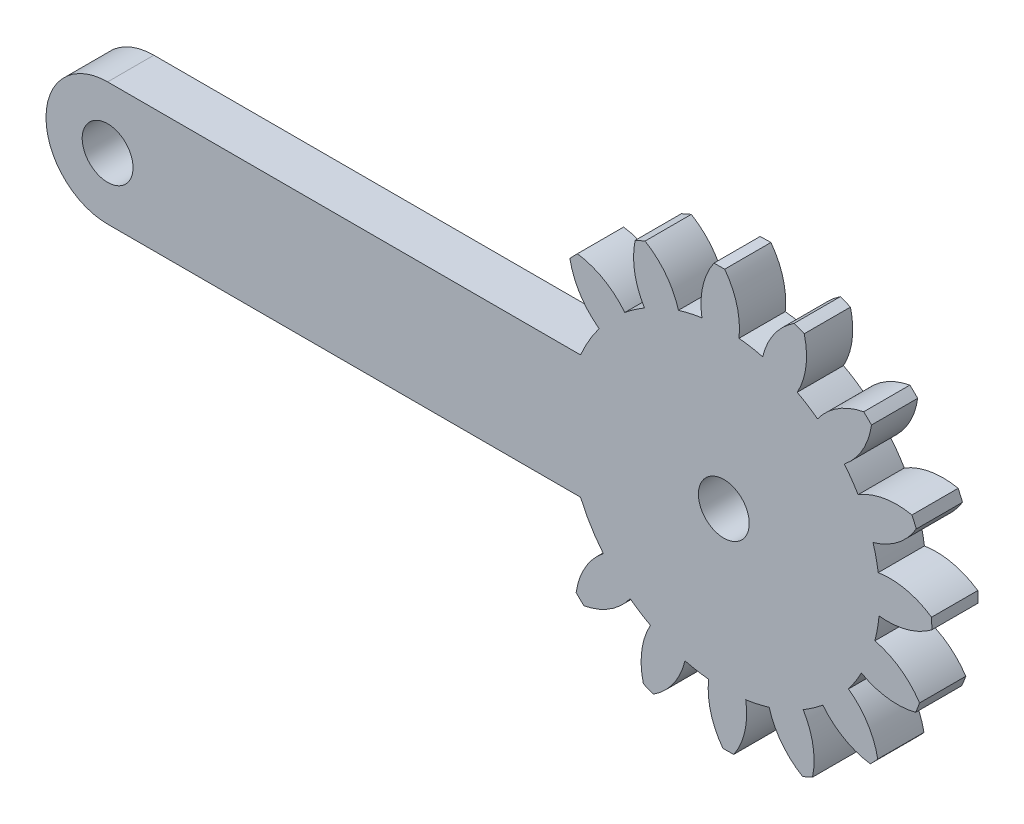
SolidWorks part; units mm, degrees
ref_plane "Front Plane" through (0, 0, 0) normal (0, 0, 1) x (1, 0, 0)
ref_plane "Top Plane" through (0, 0, 0) normal (0, 1, 0) x (1, 0, 0)
ref_plane "Right Plane" through (0, 0, 0) normal (1, 0, 0) x (0, 0, -1)
sketch "Sketch1" plane through (0, 0, 0) normal (0, 0, 1) x (1, 0, 0)
  line L0 (-12.934, -10.0504) -> (-52.934, -10.0504) construction
  line L1 (-12.934, -14.0504) -> (-52.934, -14.0504)
  line L2 (-12.934, -6.0504) -> (-52.934, -6.0504)
  arc A0 (-12.934, -14.0504) -> (-12.934, -6.0504) centre (-12.934, -10.0504) ccw
  arc A1 (-52.934, -6.0504) -> (-52.934, -14.0504) centre (-52.934, -10.0504) ccw
  circle A2 centre (-52.934, -10.0504) radius 1.65
  circle A3 centre (-12.934, -10.0504) radius 1.65
  arc A4 (-21.8661, -5.2846) -> (-21.6497, -15.2012) centre (-12.934, -10.0504) ccw
  arc A128 (0.5505, -9.4036) -> (-2.9105, -8.627) centre (-2.1566, -13.3674) ccw
  arc A129 (-2.9105, -8.627) -> (-3.2481, -7.1043) centre (-12.934, -10.0504) ccw
  arc A130 (-3.2481, -7.1043) -> (-0.4395, -4.9378) centre (-4.5681, -2.4894) ccw
  arc A131 (-0.4395, -4.9378) -> (-0.7234, -4.2925) centre (-12.934, -10.0504) ccw
  arc A132 (-0.7234, -4.2925) -> (-4.2182, -4.8995) centre (-1.7076, -8.9906) ccw
  arc A133 (-4.2182, -4.8995) -> (-5.1128, -3.622) centre (-12.934, -10.0504) ccw
  arc A134 (-5.1128, -3.622) -> (-3.3471, -0.5455) centre (-8.0984, 0.1365) ccw
  arc A135 (-3.3471, -0.5455) -> (-3.8563, -0.0581) centre (-12.934, -10.0504) ccw
  arc A136 (-3.8563, -0.0581) -> (-6.8528, -1.9562) centre (-2.9677, -4.7751) ccw
  arc A137 (-6.8528, -1.9562) -> (-8.1682, -1.1183) centre (-12.934, -10.0504) ccw
  arc A138 (-8.1682, -1.1183) -> (-7.7142, 2.3997) centre (-12.3648, 1.2116) ccw
  arc A139 (-7.7142, 2.3997) -> (-8.3712, 2.6552) centre (-12.934, -10.0504) ccw
  arc A140 (-8.3712, 2.6552) -> (-10.4132, -0.2452) centre (-5.7451, -1.3627) ccw
  arc A141 (-10.4132, -0.2452) -> (-11.9491, 0.0256) centre (-12.934, -10.0504) ccw
  arc A142 (-11.9491, 0.0256) -> (-12.876, 3.4495) centre (-16.7179, 0.5721) ccw
  arc A143 (-12.876, 3.4495) -> (-13.5807, 3.4341) centre (-12.934, -10.0504) ccw
  arc A144 (-13.5807, 3.4341) -> (-14.3574, -0.0269) centre (-9.617, 0.727) ccw
  arc A145 (-14.3574, -0.0269) -> (-15.88, -0.3645) centre (-12.934, -10.0504) ccw
  arc A146 (-15.88, -0.3645) -> (-18.0466, 2.4441) centre (-20.4949, -1.6846) ccw
  arc A147 (-18.0466, 2.4441) -> (-18.6918, 2.1602) centre (-12.934, -10.0504) ccw
  arc A148 (-18.6918, 2.1602) -> (-18.0848, -1.3346) centre (-13.9938, 1.176) ccw
  arc A149 (-18.0848, -1.3346) -> (-19.3624, -2.2292) centre (-12.934, -10.0504) ccw
  arc A150 (-19.3624, -2.2292) -> (-22.4388, -0.4635) centre (-23.1208, -5.2148) ccw
  arc A151 (-22.4388, -0.4635) -> (-22.9263, -0.9728) centre (-12.934, -10.0504) ccw
  arc A152 (-22.9263, -0.9728) -> (-21.0281, -3.9692) centre (-18.2093, -0.0841) ccw
  arc A153 (-21.0281, -3.9692) -> (-21.8661, -5.2846) centre (-12.934, -10.0504) ccw
  arc A165 (-21.6497, -15.2012) -> (-20.7551, -16.4788) centre (-12.934, -10.0504) ccw
  arc A166 (-20.7551, -16.4788) -> (-22.5208, -19.5552) centre (-17.7695, -20.2373) ccw
  arc A167 (-22.5208, -19.5552) -> (-22.0116, -20.0427) centre (-12.934, -10.0504) ccw
  arc A168 (-22.0116, -20.0427) -> (-19.0151, -18.1445) centre (-22.9002, -15.3257) ccw
  arc A169 (-19.0151, -18.1445) -> (-17.6997, -18.9825) centre (-12.934, -10.0504) ccw
  arc A170 (-17.6997, -18.9825) -> (-18.1537, -22.5005) centre (-13.5031, -21.3123) ccw
  arc A171 (-18.1537, -22.5005) -> (-17.4967, -22.7559) centre (-12.934, -10.0504) ccw
  arc A172 (-17.4967, -22.7559) -> (-15.4547, -19.8555) centre (-20.1228, -18.7381) ccw
  arc A173 (-15.4547, -19.8555) -> (-13.9188, -20.1264) centre (-12.934, -10.0504) ccw
  arc A174 (-13.9188, -20.1264) -> (-12.9919, -23.5503) centre (-9.15, -20.6729) ccw
  arc A175 (-12.9919, -23.5503) -> (-12.2872, -23.5349) centre (-12.934, -10.0504) ccw
  arc A176 (-12.2872, -23.5349) -> (-11.5106, -20.0738) centre (-16.251, -20.8278) ccw
  arc A177 (-11.5106, -20.0738) -> (-9.9879, -19.7363) centre (-12.934, -10.0504) ccw
  arc A178 (-9.9879, -19.7363) -> (-7.8214, -22.5448) centre (-5.373, -18.4162) ccw
  arc A179 (-7.8214, -22.5448) -> (-7.1761, -22.2609) centre (-12.934, -10.0504) ccw
  arc A180 (-7.1761, -22.2609) -> (-7.7831, -18.7661) centre (-11.8741, -21.2768) ccw
  arc A181 (-7.7831, -18.7661) -> (-6.5055, -17.8716) centre (-12.934, -10.0504) ccw
  arc A182 (-6.5055, -17.8716) -> (-3.4291, -19.6372) centre (-2.7471, -14.8859) ccw
  arc A183 (-3.4291, -19.6372) -> (-2.9416, -19.128) centre (-12.934, -10.0504) ccw
  arc A184 (-2.9416, -19.128) -> (-4.8398, -16.1315) centre (-7.6587, -20.0166) ccw
  arc A185 (-4.8398, -16.1315) -> (-4.0018, -14.8162) centre (-12.934, -10.0504) ccw
  arc A186 (-4.0018, -14.8162) -> (-0.4839, -15.2701) centre (-1.672, -10.6195) ccw
  arc A187 (-0.4839, -15.2701) -> (-0.2284, -14.6131) centre (-12.934, -10.0504) ccw
  arc A188 (-0.2284, -14.6131) -> (-3.1288, -12.5711) centre (-4.2463, -17.2392) ccw
  arc A189 (-3.1288, -12.5711) -> (-2.858, -11.0352) centre (-12.934, -10.0504) ccw
  arc A190 (-2.858, -11.0352) -> (0.5659, -10.1084) centre (-2.3115, -6.2664) ccw
  arc A191 (0.5659, -10.1084) -> (0.5505, -9.4036) centre (-12.934, -10.0504) ccw
  point P0 (-32.934, -10.0504)
  dimension "D4" = 3.3
  dimension "D5" = 3.3
  dimension "D2" = 40
  dimension "D3" = 8
extrude "Boss-Extrude1" add sketch "Sketch1" along normal blind 3
